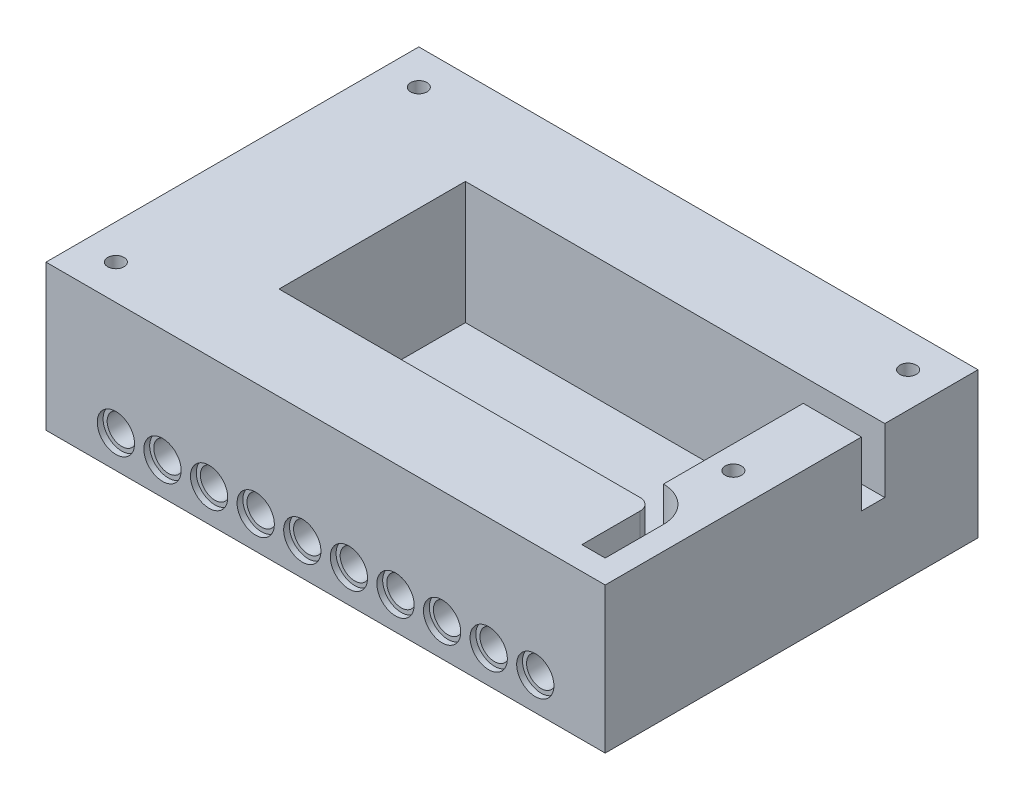
SolidWorks part; units mm, degrees
ref_plane "Front Plane" through (0, 0, 0) normal (0, 0, 1) x (1, 0, 0)
ref_plane "Top Plane" through (0, 0, 0) normal (0, 1, 0) x (1, 0, 0)
ref_plane "Right Plane" through (0, 0, 0) normal (1, 0, 0) x (0, 0, -1)
sketch "Sketch1" plane through (0, 0, 0) normal (0, 1, 0) x (1, 0, 0)
  line L1 (48, 32) -> (-48, 32)
  line L2 (48, 32) -> (48, -32)
  line L3 (48, -32) -> (-48, -32)
  line L4 (-48, 32) -> (-48, -32)
  line L5 (48, 32) -> (-48, -32) construction
  line L6 (48, -32) -> (-48, 32) construction
  point P0 (0, 0)
  dimension "D1" = 96
  dimension "D2" = 64
extrude "Boss-Extrude1" add sketch "Sketch1" along normal blind 4
sketch "Sketch2" plane through (0, 4, 0) normal (0, 1, 0) x (1, 0, 0)
  line L0 (38, 16) -> (48, 16)
  line L1 (-24, 16) -> (38, 16)
  line L2 (-24, 16) -> (-24, -16)
  line L3 (-24, -16) -> (38, -16)
  line L4 (38, 12) -> (38, -12)
  line L5 (-24, 16) -> (38, -16) construction
  line L6 (-24, -16) -> (38, 16) construction
  line L7 (48, -32) -> (48, 32) construction
  line L9 (48, 12) -> (38, 12)
  line L10 (40, -18) -> (40, -28)
  line L11 (40, -28) -> (44, -28)
  line L12 (44, -18) -> (44, -24.5345)
  line L13 (44, -24.5345) -> (44, -24.5345)
  line L14 (44, -18) -> (44, -28)
  line L15 (40, -28) -> (42.0024, -28) construction
  line L16 (-48, -32) -> (48, -32) construction
  line L17 (48, 16) -> (48, 32)
  line L18 (48, -32) -> (-48, -32)
  line L19 (48, -32) -> (48, 12)
  line L20 (48, 32) -> (-48, 32)
  line L21 (-48, -32) -> (-48, 32)
  line L22 (48, -32) -> (-48, 32) construction
  line L23 (48, 32) -> (-48, -32) construction
  arc A0 (38, -16) -> (40, -18) centre (38, -18) cw
  arc A1 (38, -12) -> (44, -18) centre (38, -18) cw
  point P0 (5.274, -0.8908)
  point P5 (7, 0)
  point P25 (0, 0)
  dimension "D1" = 62
  dimension "D2" = 32
  dimension "D3" = 4
  dimension "D5" = 4
  dimension "D6" = 10
  dimension "D7" = 4
  dimension "D4" = 4
extrude "Boss-Extrude2" add sketch "Sketch2" along normal blind 21 contours A1 L4 L9 L19 L18 L21 L20 L17 L0 L1 L2 L3 A0 L10 L11 L14
sketch "Sketch3" plane through (56, 4, -12) normal (0, -1, 0) x (1, 0, 0)
  line L1 (-18, 0) -> (-8, 0)
  line L2 (-18, 0) -> (-18, -4)
  line L3 (-18, -4) -> (-8, -4)
  line L4 (-8, 0) -> (-8, -4)
extrude "Boss-Extrude4" add sketch "Sketch3" against normal blind 10
sketch "Sketch4" plane through (0, 25, 0) normal (0, 1, 0) x (1, 0, 0)
  line L0 (48, 32) -> (-48, 32) construction
  line L1 (-48, -32) -> (-48, 32) construction
  line L2 (0, 0) -> (-16.2405, 0) construction
  line L3 (0, 1.5997) -> (0, 0) construction
  line L4 (0, 0) -> (0, 18.7096) construction
  circle A0 centre (-42, 26) radius 1.4
  circle A1 centre (-42, -26) radius 1.4
  circle A2 centre (42, 26) radius 1.4
  circle A3 centre (42, -4) radius 1.4
  dimension "D3" = 2.8
  dimension "D1" = 6
  dimension "D2" = 6
  dimension "D4" = 30
extrude "Cut-Extrude1" cut sketch "Sketch4" against normal blind 20
sketch "Sketch5" plane through (0, 0, 32) normal (0, 0, 1) x (1, 0, 0)
  line L0 (-48, 5.6) -> (48, 5.6) construction
  line L1 (-48, 25) -> (-48, 0) construction
  line L2 (48, 25) -> (48, 0) construction
  line L3 (-48, 0) -> (48, 0) construction
  line L4 (-4, 5.6) -> (4, 5.6) construction
  line L5 (-4, 5.6) -> (-4, 12.0201) construction
  line L6 (-4, 12.0201) -> (4, 12.0201) construction
  line L7 (4, 12.0201) -> (4, 5.6) construction
  circle A1 centre (-36, 5.6) radius 2.5
  circle A2 centre (-28, 5.6) radius 2.5
  circle A3 centre (-20, 5.6) radius 2.5
  circle A4 centre (-12, 5.6) radius 2.5
  circle A5 centre (-4, 5.6) radius 2.5
  circle A6 centre (4, 5.6) radius 2.5
  circle A7 centre (12, 5.6) radius 2.5
  circle A8 centre (20, 5.6) radius 2.5
  circle A9 centre (28, 5.6) radius 2.5
  circle A10 centre (36, 5.6) radius 2.5
  point P5 (0, 12.0201)
  point P33 (0, 5.6)
  dimension "D2" = 5
  dimension "D1" = 5.6
  dimension "D4" = 8
extrude "Cut-Extrude2" cut sketch "Sketch5" against normal blind 10
sketch "Sketch7" plane through (0, 0, 32) normal (0, 0, 1) x (1, 0, 0)
  circle A0 centre (-36, 5.6) radius 3.2
  circle A1 centre (-28, 5.6) radius 3.2
  circle A2 centre (-20, 5.6) radius 3.2
  circle A3 centre (-12, 5.6) radius 3.2
  circle A4 centre (-4, 5.6) radius 3.2
  circle A5 centre (4, 5.6) radius 3.2
  circle A6 centre (12, 5.6) radius 3.2
  circle A7 centre (20, 5.6) radius 3.2
  circle A8 centre (28, 5.6) radius 3.2
  circle A9 centre (36, 5.6) radius 3.2
  dimension "D2" = 6.4
  dimension "D1" = 10
extrude "Cut-Extrude3" cut sketch "Sketch7" against normal blind 1 contours A6 | A5 | A4 | A3 | A2 | A0 | A1 | A9 | A8 | A7
mirror "Mirror1" about plane through (0, 0, 0) normal (0, 0, 1) of "Cut-Extrude3", "Cut-Extrude2"
